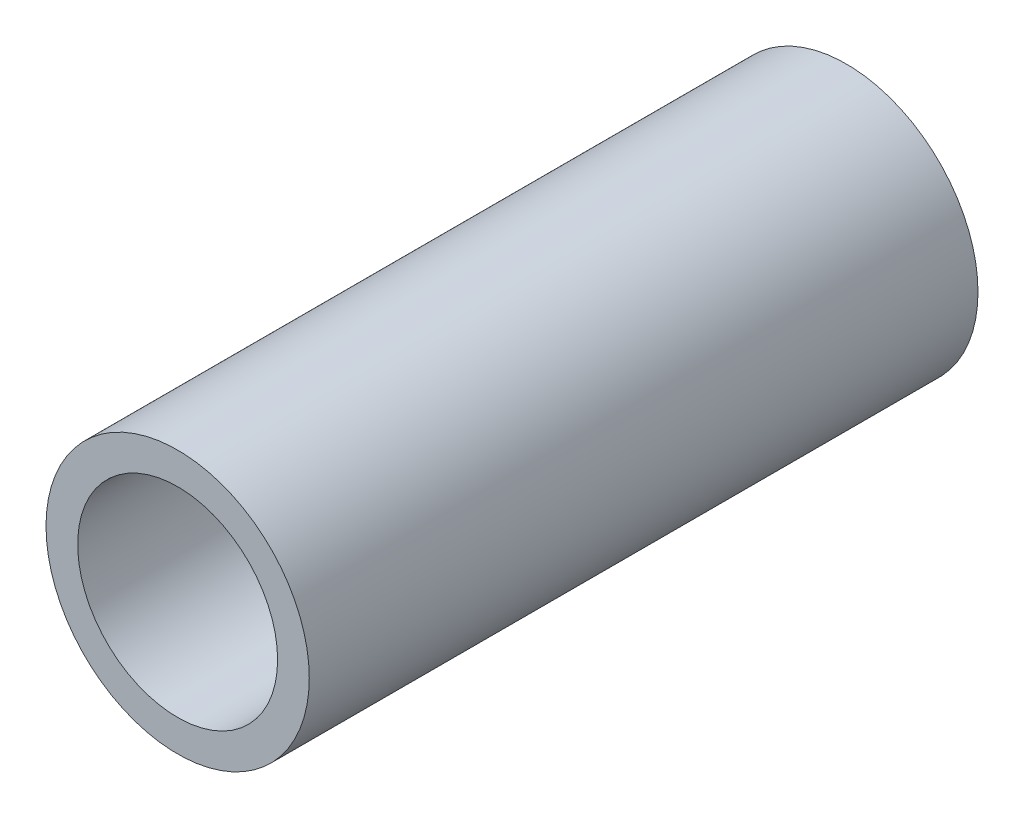
SolidWorks part; units mm, degrees
ref_plane "Front Plane" through (0, 0, 0) normal (0, 0, 1) x (1, 0, 0)
ref_plane "Top Plane" through (0, 0, 0) normal (0, 1, 0) x (1, 0, 0)
ref_plane "Right Plane" through (0, 0, 0) normal (1, 0, 0) x (0, 0, -1)
sketch "Sketch1" plane through (0, 0, 0) normal (0, 0, 1) x (1, 0, 0)
  circle A0 centre (0, 0) radius 2.5
  dimension "D1" = 5
extrude "Boss-Extrude1" add sketch "Sketch1" along normal blind 12.7
hole_wizard "#6 Clearance Hole1" positions "Sketch3" profile "Sketch2" hole size "#6" standard "ANSI Inch" end condition through all
sketch "Sketch3" plane through (0, 0, 12.7) normal (0, 0, 1) x (1, 0, 0)
  point P0 (0, 0)
sketch "Sketch2" plane through (0, 0, 12.7) normal (1, 0, 0) x (0, -1, 0)
  line L0 (0, 0) -> (0, 12.7)
  line L1 (0, 12.7) -> (1.8986, 12.7)
  line L2 (1.8986, 12.7) -> (1.8986, 0)
  line L5 (1.8986, 0) -> (0, 0)
  line L11 (0, -6.35) -> (0, 107.95) construction
  dimension "Thru Hole Dia." = 3.7973
  dimension "Thru Hole Depth" = 12.7
